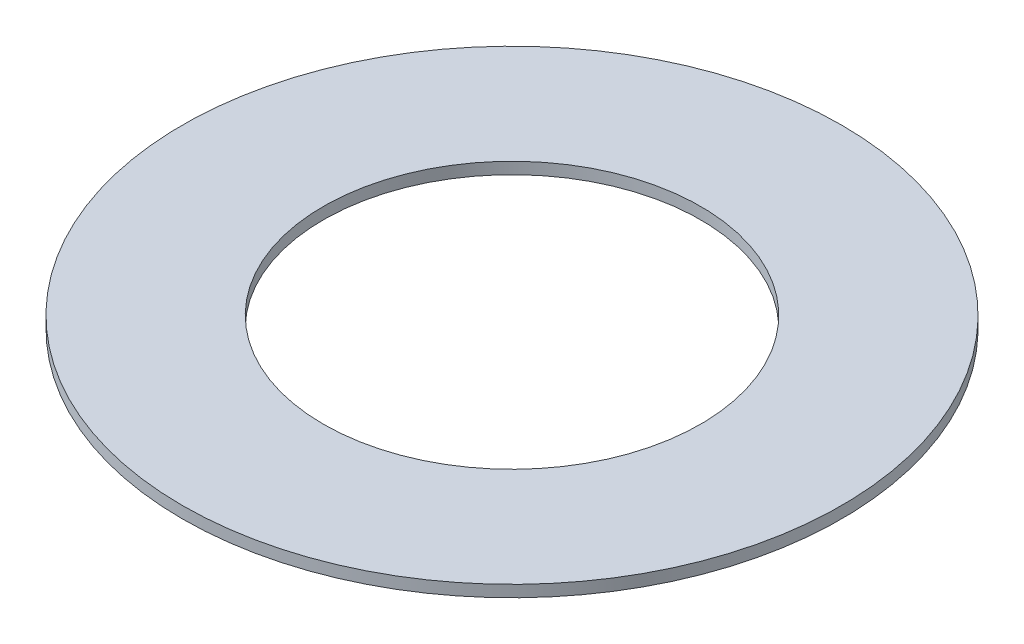
SolidWorks part; units mm, degrees
ref_plane "Front Plane" through (0, 0, 0) normal (0, 0, 1) x (1, 0, 0)
ref_plane "Top Plane" through (0, 0, 0) normal (0, 1, 0) x (1, 0, 0)
ref_plane "Right Plane" through (0, 0, 0) normal (1, 0, 0) x (0, 0, -1)
sketch "Sketch1" plane through (0, 0, 0) normal (0, 1, 0) x (1, 0, 0)
  circle A0 centre (0, 0) radius 8.1
  circle A1 centre (0, 0) radius 14.15
  dimension "D1" = 16.2
  dimension "D2" = 28.3
extrude "Boss-Extrude1" add sketch "Sketch1" along normal blind 0.5
